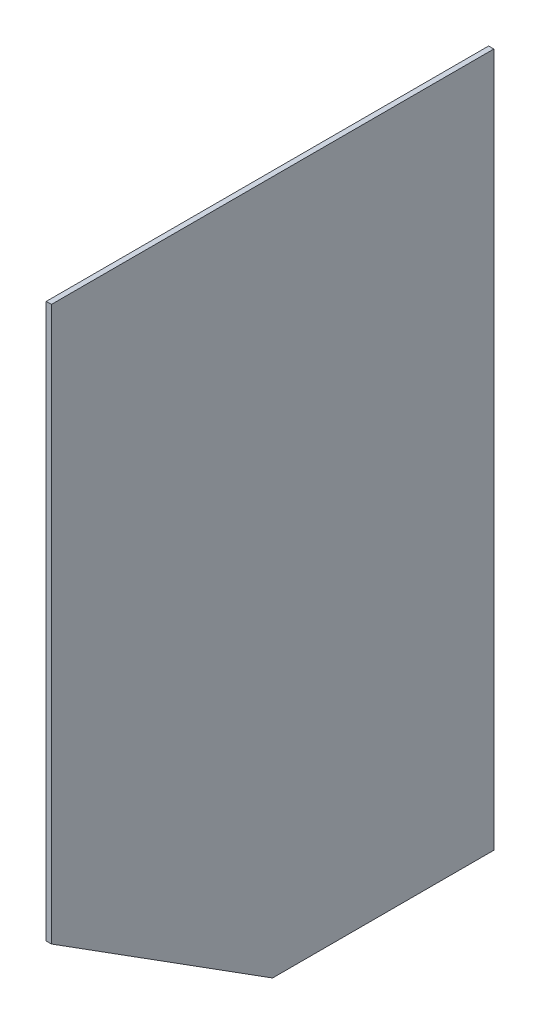
SolidWorks part; units mm, degrees
ref_plane "Front Plane" through (0, 0, 0) normal (0, 0, 1) x (1, 0, 0)
ref_plane "Top Plane" through (0, 0, 0) normal (0, 1, 0) x (1, 0, 0)
ref_plane "Right Plane" through (0, 0, 0) normal (1, 0, 0) x (0, 0, -1)
sketch "Sketch1" plane through (0, 0, 0) normal (0, 0, 1) x (1, 0, 0)
  line L0 (-137.6995, 269.2927) -> (-137.6995, -130.7073)
  line L1 (-137.6995, -130.7073) -> (-140.6995, -130.7073)
  line L2 (-140.6995, -130.7073) -> (-140.6995, 269.2927)
  line L3 (-140.6995, 269.2927) -> (-137.6995, 269.2927)
  ellipse E0 centre (-117.991, -168.7633) end of major axis (-115.1769, -168.7633) minor radius 1.221 construction
  ellipse E1 centre (-117.991, -168.7633) end of major axis (-115.1769, -168.7633) minor radius 1.221
  spline S0 degree 3 poles (-120.7377, 269.2254) (-120.7377, 266.8419) (-115.2442, 266.8419) (-115.2442, 269.2254) (-115.2442, 271.6089) (-120.7377, 271.6089) (-120.7377, 269.2254) (-120.7377, 266.8419) (-115.2442, 266.8419) knots -0.5 0 0 0 0.5 0.5 0.5 1 1 1 1.5 1.5 1.5 weights 1 0.333333 0.333333 1 0.333333 0.333333 1 0.333333 0.333333 only from (-120.7377, 269.2254) to (-120.7377, 269.2254) construction
  spline S1 degree 3 poles (-120.7377, 269.2254) (-120.7377, 266.8419) (-115.2442, 266.8419) (-115.2442, 269.2254) (-115.2442, 271.6089) (-120.7377, 271.6089) (-120.7377, 269.2254) (-120.7377, 266.8419) (-115.2442, 266.8419) knots -0.5 0 0 0 0.5 0.5 0.5 1 1 1 1.5 1.5 1.5 weights 1 0.333333 0.333333 1 0.333333 0.333333 1 0.333333 0.333333 only from (-120.7377, 269.2254) to (-120.7377, 269.2254)
  spline S2 degree 3 poles (-120.7377, 269.2254) (-120.7377, 266.8419) (-115.2442, 266.8419) (-115.2442, 269.2254) (-115.2442, 271.6089) (-120.7377, 271.6089) (-120.7377, 269.2254) (-120.7377, 266.8419) (-115.2442, 266.8419) knots -0.5 0 0 0 0.5 0.5 0.5 1 1 1 1.5 1.5 1.5 weights 1 0.333333 0.333333 1 0.333333 0.333333 1 0.333333 0.333333 only from (-120.7377, 269.2254) to (-120.7377, 269.2254)
  spline S3 degree 3 poles (-120.7377, 269.2254) (-120.7377, 266.8419) (-115.2442, 266.8419) (-115.2442, 269.2254) (-115.2442, 271.6089) (-120.7377, 271.6089) (-120.7377, 269.2254) (-120.7377, 266.8419) (-115.2442, 266.8419) knots -0.5 0 0 0 0.5 0.5 0.5 1 1 1 1.5 1.5 1.5 weights 1 0.333333 0.333333 1 0.333333 0.333333 1 0.333333 0.333333 only from (-120.7377, 269.2254) to (-120.7377, 269.2254)
extrude "Boss-Extrude1" add sketch "Sketch1" against normal blind 255 contours L3 L2 L1 L0
sketch "Sketch2" plane through (-140.6995, 0, 0) normal (-1, 0, 0) x (0, 0, 1)
  line L0 (0, 0) -> (0, -50)
  line L2 (0, -130.7073) -> (0, 269.2927) construction
  line L3 (0, -50) -> (-127.5, -130.7073)
  line L4 (-255, -130.7073) -> (0, -130.7073) construction
  line L5 (-127.5, -130.7073) -> (0, -130.7073)
  line L6 (0, -130.7073) -> (0, -50)
  line M1 (0, -130.7073) -> (0, 269.2927)
  line M4 (-255, -130.7073) -> (0, -130.7073)
extrude "Cut-Extrude1" cut sketch "Sketch2" against normal through all contours L3 M1 M4
